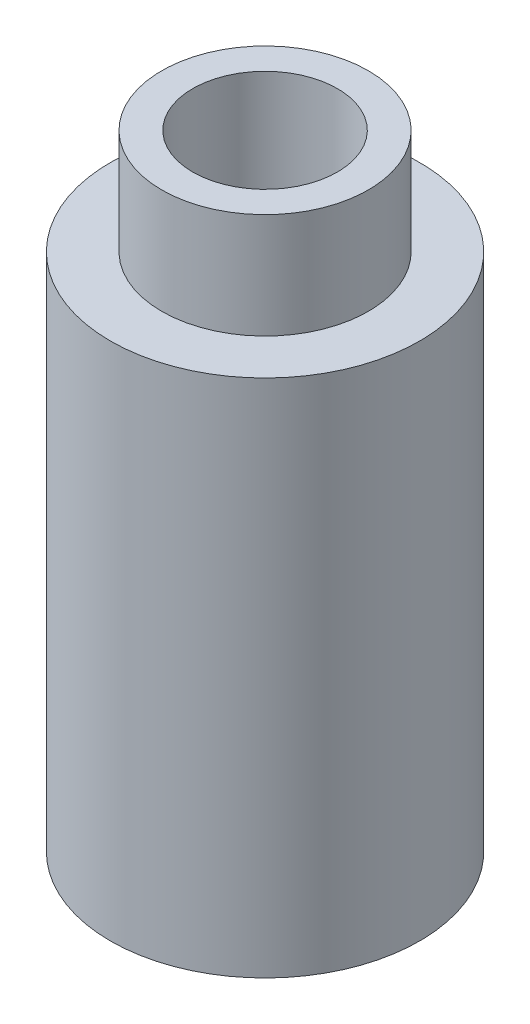
SolidWorks part; units mm, degrees
ref_plane "Front Plane" through (0, 0, 0) normal (0, 0, 1) x (1, 0, 0)
ref_plane "Top Plane" through (0, 0, 0) normal (0, 1, 0) x (1, 0, 0)
ref_plane "Right Plane" through (0, 0, 0) normal (1, 0, 0) x (0, 0, -1)
sketch "Sketch1" plane through (0, 0, 0) normal (0, 1, 0) x (1, 0, 0)
  circle A0 centre (0, 0) radius 9.4488
  dimension "D1" = 18.8976
extrude "Boss-Extrude1" add sketch "Sketch1" along normal blind 31.75
sketch "Sketch2" plane through (0, 31.75, 0) normal (0, 1, 0) x (1, 0, 0)
  circle A0 centre (0, 0) radius 6.3119
  dimension "D1" = 12.6238
extrude "Boss-Extrude2" add sketch "Sketch2" along normal blind 6.4262
sketch "Sketch3" plane through (0, 38.1762, 0) normal (0, 1, 0) x (1, 0, 0)
  circle A0 centre (0, 0) radius 4.4196
  dimension "D1" = 8.8392
extrude "Cut-Extrude1" cut sketch "Sketch3" against normal through all
